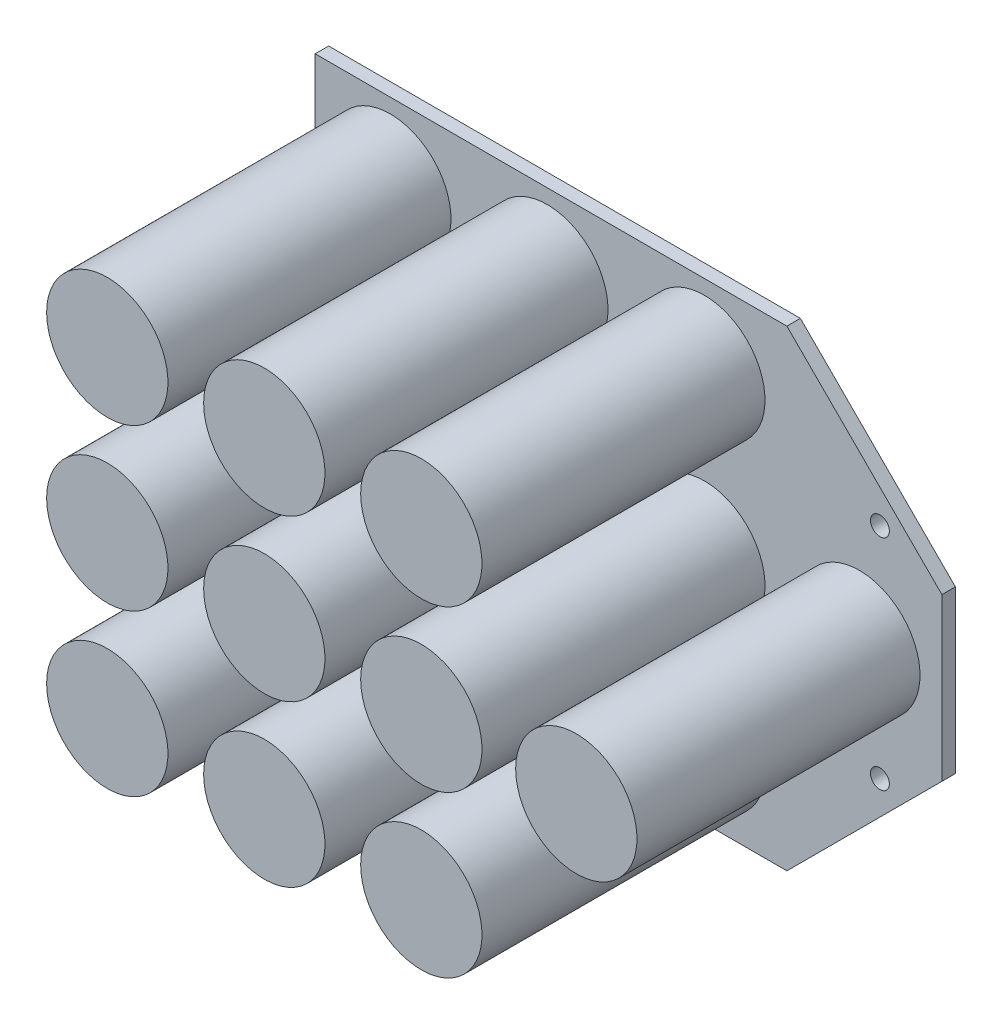
SolidWorks part; units mm, degrees
ref_plane "前视基准面" through (0, 0, 0) normal (0, 0, 1) x (1, 0, 0)
ref_plane "上视基准面" through (0, 0, 0) normal (0, 1, 0) x (1, 0, 0)
ref_plane "右视基准面" through (0, 0, 0) normal (1, 0, 0) x (0, 0, -1)
sketch "草图1" plane through (0, 0, 0) normal (0, 0, 1) x (1, 0, 0)
  line L0 (23.5, 35) -> (46.5, 12)
  line L1 (-46.5, 35) -> (46.5, 35)
  line L2 (-46.5, 35) -> (-46.5, -35)
  line L3 (-46.5, -35) -> (46.5, -35)
  line L4 (46.5, 35) -> (46.5, -35)
  line L5 (0, -35) -> (0, 35) construction
  line L6 (-46.5, 0) -> (46.5, 0) construction
  line L7 (23.5, -35) -> (46.5, -12)
  point P0 (0, 0)
  point P7 (45.1642, 12.2165)
  dimension "D1" = 70
  dimension "D2" = 93
  dimension "D3" = 24
  dimension "D4" = 90
extrude "凸台-拉伸1" add sketch "草图1" along normal blind 2 contours L3 L7 L4 L0 L1 L2
sketch "草图3" plane through (0, 0, 2) normal (0, 0, 1) x (1, 0, 0)
  line L0 (-56.0623, 0) -> (62.9526, 0) construction
  line L3 (-46.5, 35) -> (-46.5, -35) construction
  circle A0 centre (-22.9, 16.25) radius 1.4
  circle A1 centre (37.3, 16.25) radius 1.4
  circle A2 centre (37.3, -16.25) radius 1.4
  circle A3 centre (-22.9, -16.25) radius 1.4
  point P9 (0, 0)
  dimension "D1" = 2.8
  dimension "D2" = 2.8
  dimension "D3" = 22.2
  dimension "D4" = 63
  dimension "D5" = 32.5
extrude "切除-拉伸1" cut sketch "草图3" against normal blind 2
sketch "草图4" plane through (0, 0, 2) normal (0, 0, 1) x (1, 0, 0)
  line L0 (-46.5, 35) -> (-46.5, -35) construction
  line L1 (-46.5, -35) -> (23.5, -35) construction
  line L2 (-46.5, 35) -> (23.5, 35) construction
  circle A0 centre (-35.35, -23.85) radius 11.15 construction
  circle A1 centre (-12.05, -23.85) radius 11.15 construction
  circle A2 centre (11.25, -23.85) radius 11.15 construction
  circle A3 centre (-12.05, 0) radius 11.15 construction
  circle A4 centre (11.25, 0) radius 11.15 construction
  circle A5 centre (-12.05, 23.85) radius 11.15 construction
  circle A6 centre (11.25, 23.85) radius 11.15 construction
  circle A7 centre (-35.35, 0) radius 11.15 construction
  circle A8 centre (-35.35, 23.85) radius 11.15 construction
  circle A9 centre (-35.35, -23.85) radius 9
  circle A10 centre (-12.05, -23.85) radius 9
  circle A11 centre (11.25, -23.85) radius 9
  circle A12 centre (-12.05, 0) radius 9
  circle A13 centre (11.25, 0) radius 9
  circle A14 centre (-12.05, 23.85) radius 9
  circle A15 centre (11.25, 23.85) radius 9
  circle A16 centre (-35.35, 0) radius 9
  circle A17 centre (-35.35, 23.85) radius 9
  circle A18 centre (34.25, 0) radius 9
  point P7 (35.3823, 0)
  dimension "D1" = 22.3
  dimension "D4" = 1
  dimension "D5" = 18
  dimension "D8" = 18
  dimension "D9" = 23
  dimension "D2" = 3
  dimension "D3" = 3
  dimension "D6" = 3
  dimension "D7" = 3
extrude "凸台-拉伸2" add sketch "草图4" along normal blind 42
